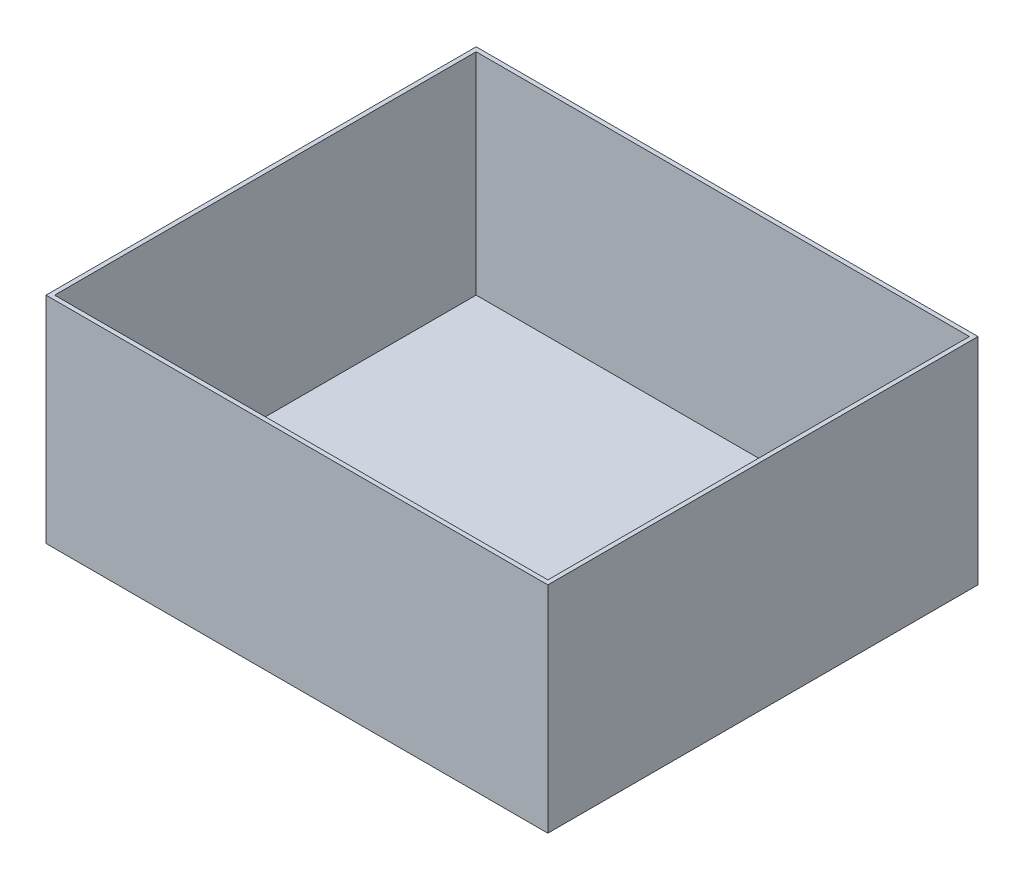
SolidWorks part; units mm, degrees
ref_plane "前视基准面" through (0, 0, 0) normal (0, 0, 1) x (1, 0, 0)
ref_plane "上视基准面" through (0, 0, 0) normal (0, 1, 0) x (1, 0, 0)
ref_plane "右视基准面" through (0, 0, 0) normal (1, 0, 0) x (0, 0, -1)
sketch "草图1" plane through (0, 0, 0) normal (0, 1, 0) x (1, 0, 0)
  line L1 (-175, -150) -> (175, -150)
  line L2 (-175, -150) -> (-175, 150)
  line L3 (-175, 150) -> (175, 150)
  line L4 (175, -150) -> (175, 150)
  line L5 (-175, -150) -> (175, 150) construction
  line L6 (-175, 150) -> (175, -150) construction
  point P0 (0, 0)
  point P6 (175, 0)
  dimension "D1" = 350
  dimension "D2" = 300
extrude "拉伸-薄壁1" add sketch "草图1" along normal blind 150 thin contours L1 L4 L3 L2 thin type one direction reverse wall 3
sketch "草图2" plane through (0, 0, 0) normal (0, -1, 0) x (1, 0, 0)
  line L1 (-175, -150) -> (175, -150)
  line L2 (-175, -150) -> (-175, 150)
  line L3 (-175, 150) -> (175, 150)
  line L4 (175, -150) -> (175, 150)
extrude "凸台-拉伸1" add sketch "草图2" against normal blind 3
